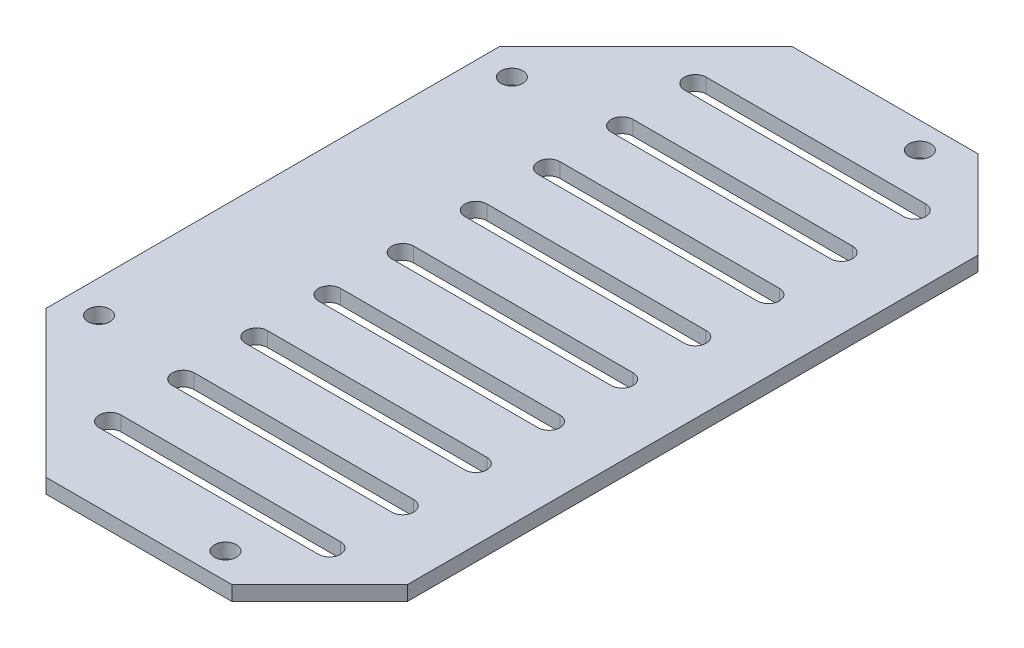
SolidWorks part; units mm, degrees
ref_plane "前视基准面" through (0, 0, 0) normal (0, 0, 1) x (1, 0, 0)
ref_plane "上视基准面" through (0, 0, 0) normal (0, 1, 0) x (1, 0, 0)
ref_plane "右视基准面" through (0, 0, 0) normal (1, 0, 0) x (0, 0, -1)
sketch "Sketch1" plane through (0, 0, 0) normal (0, 1, 0) x (1, 0, 0)
  line L8 (-25.8338, 95.7032) -> (11.5762, 95.7032)
  line L9 (11.5762, -6.3018) -> (-25.8338, -6.3018)
  line L10 (-45.8338, 75.7032) -> (-25.8338, 95.7032)
  line L11 (-25.8338, -6.3018) -> (-45.8338, 13.6982)
  line L12 (-45.8338, 13.6982) -> (-45.8338, 75.7032)
  line L13 (11.5762, -6.3018) -> (11.5762, 95.7032)
  line L14 (1.9255, 44.7007) -> (-28.0745, 44.7007) construction
  line L15 (1.9255, 43.2007) -> (-28.0745, 43.2007)
  line L16 (1.9255, 46.2007) -> (-28.0745, 46.2007)
  line L17 (-45.8338, 44.7007) -> (-145.6421, 44.7007) construction
  line L19 (1.9255, 54.7007) -> (-28.0745, 54.7007) construction
  line L20 (1.9255, 53.2007) -> (-28.0745, 53.2007)
  line L21 (1.9255, 56.2007) -> (-28.0745, 56.2007)
  line L23 (1.9255, 64.7007) -> (-28.0745, 64.7007) construction
  line L24 (1.9255, 63.2007) -> (-28.0745, 63.2007)
  line L25 (1.9255, 66.2007) -> (-28.0745, 66.2007)
  line L27 (1.9255, 74.7007) -> (-28.0745, 74.7007) construction
  line L28 (1.9255, 73.2007) -> (-28.0745, 73.2007)
  line L29 (1.9255, 76.2007) -> (-28.0745, 76.2007)
  line L31 (1.9255, 84.7007) -> (-28.0745, 84.7007) construction
  line L32 (1.9255, 83.2007) -> (-28.0745, 83.2007)
  line L33 (1.9255, 86.2007) -> (-28.0745, 86.2007)
  line L34 (1.9255, 36.2007) -> (-28.0745, 36.2007)
  line L35 (1.9255, 33.2007) -> (-28.0745, 33.2007)
  line L36 (1.9255, 34.7007) -> (-28.0745, 34.7007) construction
  line L37 (1.9255, 26.2007) -> (-28.0745, 26.2007)
  line L38 (1.9255, 23.2007) -> (-28.0745, 23.2007)
  line L39 (1.9255, 24.7007) -> (-28.0745, 24.7007) construction
  line L40 (1.9255, 16.2007) -> (-28.0745, 16.2007)
  line L41 (1.9255, 13.2007) -> (-28.0745, 13.2007)
  line L42 (1.9255, 14.7007) -> (-28.0745, 14.7007) construction
  line L43 (1.9255, 6.2007) -> (-28.0745, 6.2007)
  line L44 (1.9255, 3.2007) -> (-28.0745, 3.2007)
  line L45 (1.9255, 4.7007) -> (-28.0745, 4.7007) construction
  line L46 (-45.8338, 53.6982) -> (-45.8338, 115.7032) [skipped]
  line L47 (-45.8338, 33.6982) -> (-45.8338, 95.7032) [skipped]
  line L48 (-45.8338, 43.6982) -> (-45.8338, 105.7032) [skipped]
  line L49 (-45.8338, 23.6982) -> (-45.8338, 85.7032) [skipped]
  arc A0 (1.9255, 43.2007) -> (1.9255, 46.2007) centre (1.9255, 44.7007) ccw
  arc A1 (-28.0745, 46.2007) -> (-28.0745, 43.2007) centre (-28.0745, 44.7007) ccw
  arc A2 (1.9255, 53.2007) -> (1.9255, 56.2007) centre (1.9255, 54.7007) ccw
  arc A3 (-28.0745, 56.2007) -> (-28.0745, 53.2007) centre (-28.0745, 54.7007) ccw
  arc A4 (1.9255, 63.2007) -> (1.9255, 66.2007) centre (1.9255, 64.7007) ccw
  arc A5 (-28.0745, 66.2007) -> (-28.0745, 63.2007) centre (-28.0745, 64.7007) ccw
  arc A6 (1.9255, 73.2007) -> (1.9255, 76.2007) centre (1.9255, 74.7007) ccw
  arc A7 (-28.0745, 76.2007) -> (-28.0745, 73.2007) centre (-28.0745, 74.7007) ccw
  arc A8 (1.9255, 83.2007) -> (1.9255, 86.2007) centre (1.9255, 84.7007) ccw
  arc A9 (-28.0745, 86.2007) -> (-28.0745, 83.2007) centre (-28.0745, 84.7007) ccw
  arc A10 (1.9255, 33.2007) -> (1.9255, 36.2007) centre (1.9255, 34.7007) ccw
  arc A11 (-28.0745, 36.2007) -> (-28.0745, 33.2007) centre (-28.0745, 34.7007) ccw
  arc A12 (1.9255, 23.2007) -> (1.9255, 26.2007) centre (1.9255, 24.7007) ccw
  arc A13 (-28.0745, 26.2007) -> (-28.0745, 23.2007) centre (-28.0745, 24.7007) ccw
  arc A14 (1.9255, 13.2007) -> (1.9255, 16.2007) centre (1.9255, 14.7007) ccw
  arc A15 (-28.0745, 16.2007) -> (-28.0745, 13.2007) centre (-28.0745, 14.7007) ccw
  arc A16 (1.9255, 3.2007) -> (1.9255, 6.2007) centre (1.9255, 4.7007) ccw
  arc A17 (-28.0745, 6.2007) -> (-28.0745, 3.2007) centre (-28.0745, 4.7007) ccw
  point P8 (-13.0745, 44.7007)
  point P21 (-13.0745, 54.7007)
  point P30 (-13.0745, 64.7007)
  point P39 (-13.0745, 74.7007)
  point P48 (-13.0745, 84.7007)
  point P54 (-13.0745, 34.7007)
  point P61 (-13.0745, 24.7007)
  point P68 (-13.0745, 14.7007)
  point P75 (-13.0745, 4.7007)
  dimension "D1" = 3
  dimension "D2" = 30
  dimension "D3" = 5
  dimension "D4" = 5
extrude "Boss-Extrude1" add sketch "Sketch1" along normal blind 2
chamfer "Chamfer1" distance 12 angle 45 2 edges at (11.5762, 1, 6.3018) (11.5762, 1, -95.7032)
sketch "Sketch2" plane through (0, 2, 0) normal (0, 1, 0) x (1, 0, 0)
  line L0 (11.5762, 44.7007) -> (-48.6917, 44.7007) construction
  circle A0 centre (-4.8388, 92.1666) radius 1.5
  circle A1 centre (-41.3714, 72.9217) radius 1.5
  circle A2 centre (-41.3714, 16.4797) radius 1.5
  circle A3 centre (-4.8388, -2.7652) radius 1.5
extrude "Cut-Extrude1" cut sketch "Sketch2" against normal blind 10
